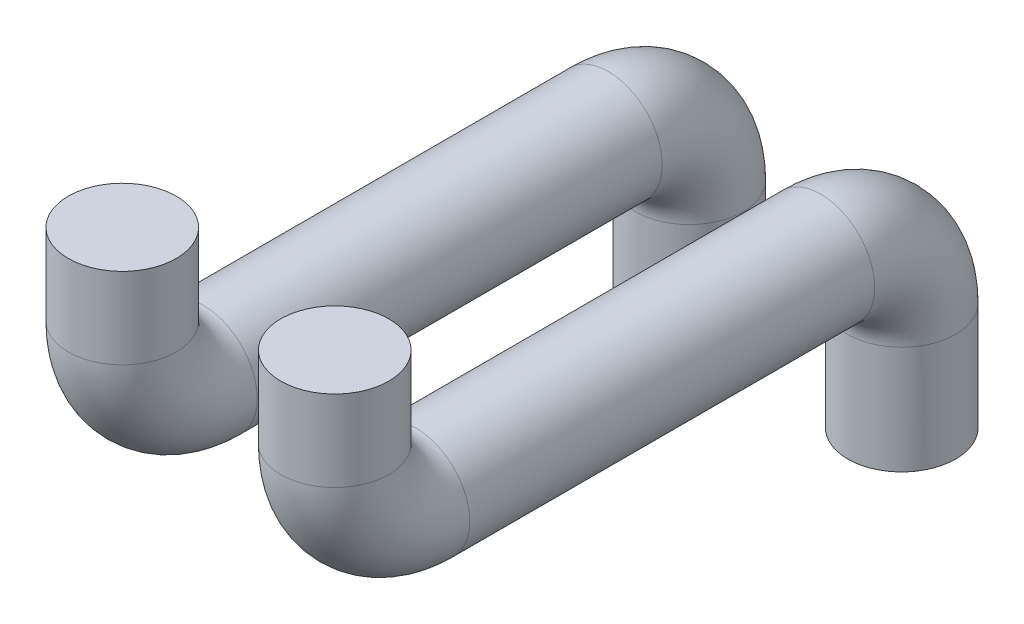
SolidWorks part; units mm, degrees
material "1060 Alloy"
ref_plane "Front Plane" through (0, 0, 0) normal (0, 0, 1) x (1, 0, 0)
ref_plane "Top Plane" through (0, 0, 0) normal (0, 1, 0) x (1, 0, 0)
ref_plane "Right Plane" through (0, 0, 0) normal (1, 0, 0) x (0, 0, -1)
sketch "Sketch1" plane through (0, 0, 0) normal (1, 0, 0) x (0, 0, -1)
  line L0 (-10.5, 6) -> (-10.5, 3)
  line L1 (-7.5, 0) -> (7.5, 0)
  line L2 (10.5, -3) -> (10.5, -7)
  arc A0 (10.5, -3) -> (7.5, 0) centre (7.5, -3) ccw
  arc A1 (-7.5, 0) -> (-10.5, 3) centre (-7.5, 3) cw
  point P9 (-33.627, 15.6077)
  point P10 (-34.2178, 10)
  point P11 (-33.9389, 7)
  dimension "D1" = 3
  dimension "D3" = 15
  dimension "D2" = 6
  dimension "D4" = 7
ref_plane "Plane1" through (0, 6, 0) normal (0, 1, 0) x (1, 0, 0)
sketch "Sketch2" plane through (0, 6, 0) normal (0, 1, 0) x (1, 0, 0)
  circle A0 centre (0, -10.5) radius 2
  dimension "D1" = 4
sweep "Sweep1" add profiles "Sketch2" path "Sketch1"
ref_plane "Plane2" through (-3.935, 0, 0) normal (1, 0, 0) x (0, 0, -1)
mirror "Mirror2" about plane through (-3.935, 0, 0) normal (1, 0, 0) of bodies 101
